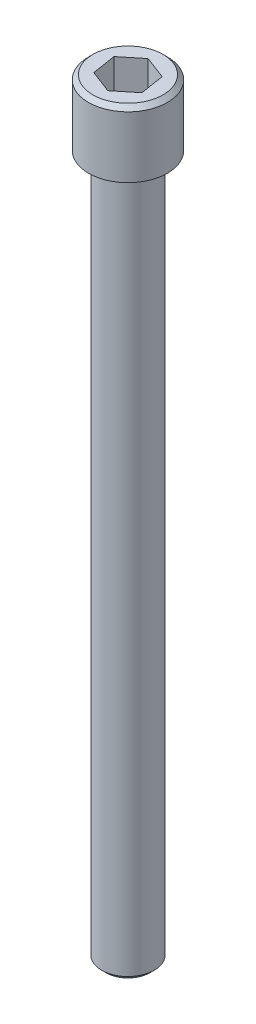
SolidWorks part; units mm, degrees
ref_plane "Přední rovina" through (0, 0, 0) normal (0, 0, 1) x (1, 0, 0)
ref_plane "Horní rovina" through (0, 0, 0) normal (0, 1, 0) x (1, 0, 0)
ref_plane "Pravá rovina" through (0, 0, 0) normal (1, 0, 0) x (0, 0, -1)
sketch "Skica1" plane through (0, 0, 0) normal (0, 1, 0) x (1, 0, 0)
  circle A0 centre (0, 0) radius 1.5
  dimension "D1" = 3
extrude "Přidat vysunutím1" add sketch "Skica1" along normal blind 40
sketch "Skica2" plane through (0, 40, 0) normal (0, 1, 0) x (1, 0, 0)
  circle A0 centre (0, 0) radius 2.25
  dimension "D1" = 4.5
extrude "Přidat vysunutím2" add sketch "Skica2" along normal blind 3.75
sketch "Skica3" plane through (0, 43.75, 0) normal (0, 1, 0) x (1, 0, 0)
  line L1 (-1.0744, -0.875) -> (0.2206, -1.368)
  line L2 (0.2206, -1.368) -> (1.295, -0.493)
  line L3 (1.295, -0.493) -> (1.0744, 0.875)
  line L4 (1.0744, 0.875) -> (-0.2206, 1.368)
  line L5 (-0.2206, 1.368) -> (-1.295, 0.493)
  line L6 (-1.295, 0.493) -> (-1.0744, -0.875)
  circle A0 centre (0, 0) radius 1.2 construction
  dimension "D1" = 2.4
extrude "Odebrat vysunutím1" cut sketch "Skica3" against normal blind 2.25
chamfer "Zkosení1" distance 0.25 angle 45 1 edges at (0, 43.75, 2.25)
chamfer "Zkosení2" distance 0.25 angle 45 1 edges at (0, 0, 1.5)
